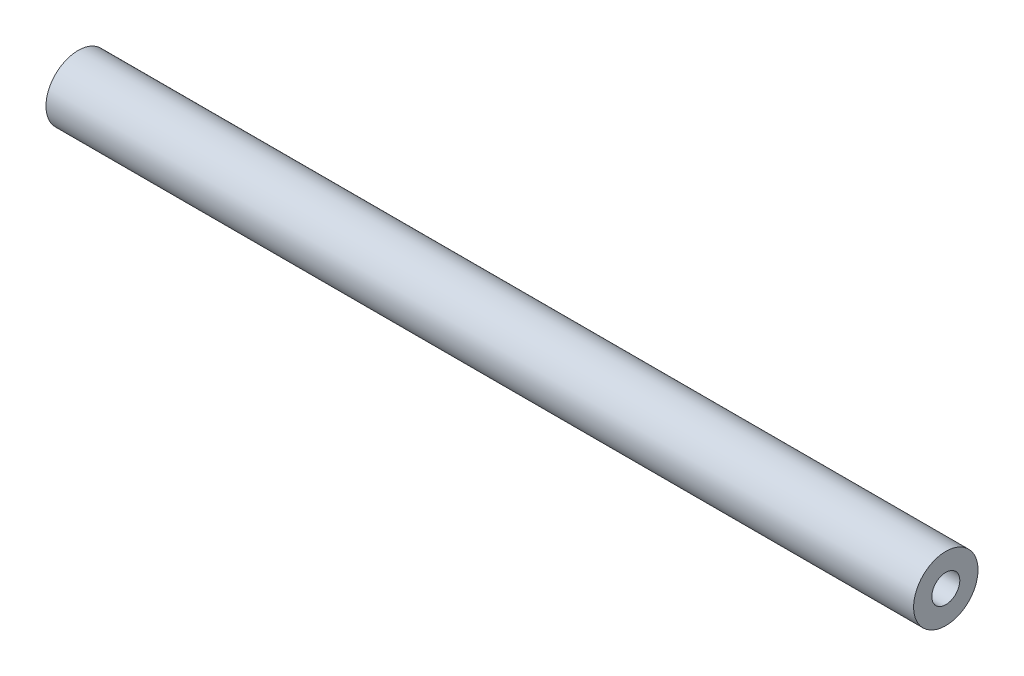
SolidWorks part; units mm, degrees
ref_plane "Front Plane" through (0, 0, 0) normal (0, 0, 1) x (1, 0, 0)
ref_plane "Top Plane" through (0, 0, 0) normal (0, 1, 0) x (1, 0, 0)
ref_plane "Right Plane" through (0, 0, 0) normal (1, 0, 0) x (0, 0, -1)
sketch "Sketch1" plane through (0, 0, 0) normal (1, 0, 0) x (0, 0, -1)
  circle A0 centre (0, 0) radius 11.5
  circle A1 centre (0, 0) radius 5
  dimension "D1" = 23
  dimension "D2" = 10
extrude "Boss-Extrude1" add sketch "Sketch1" along normal blind 310
